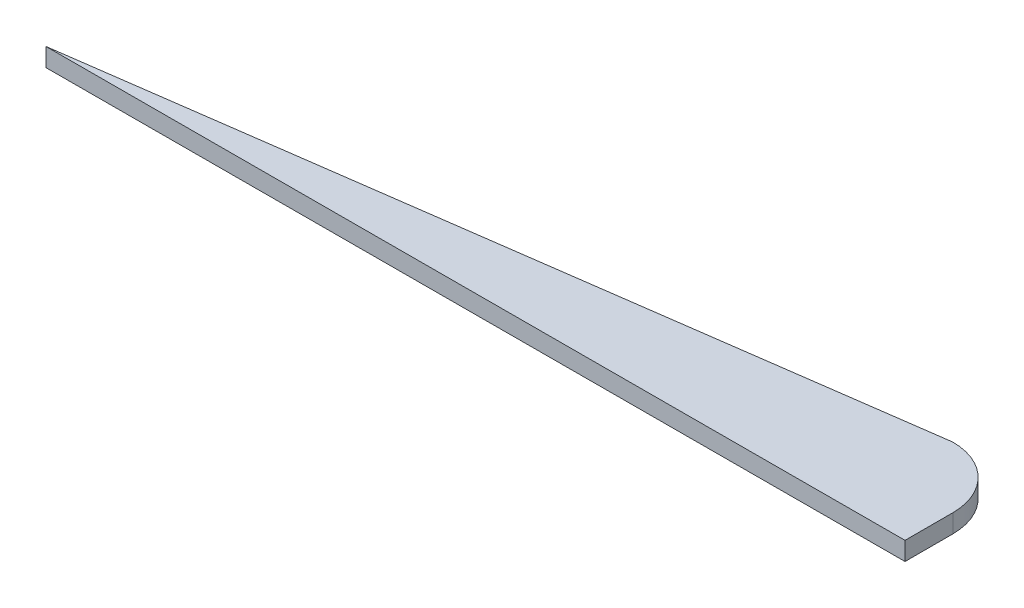
SolidWorks part; units mm, degrees
ref_plane "Front Plane" through (0, 0, 0) normal (0, 0, 1) x (1, 0, 0)
ref_plane "Top Plane" through (0, 0, 0) normal (0, 1, 0) x (1, 0, 0)
ref_plane "Right Plane" through (0, 0, 0) normal (1, 0, 0) x (0, 0, -1)
sketch "Sketch1" plane through (0, 0, 0) normal (0, 1, 0) x (1, 0, 0)
  line L0 (39.0375, 12.2433) -> (39.0375, 27.8433)
  line L3 (-240.9625, 11.6433) -> (19.0375, 47.8433)
  line L4 (-240.9625, 11.6433) -> (39.0375, 12.2433)
  arc A0 (19.0375, 47.8433) -> (39.0375, 27.8433) centre (19.0375, 27.8433) cw
extrude "Boss-Extrude2" add sketch "Sketch1" along normal blind 6
